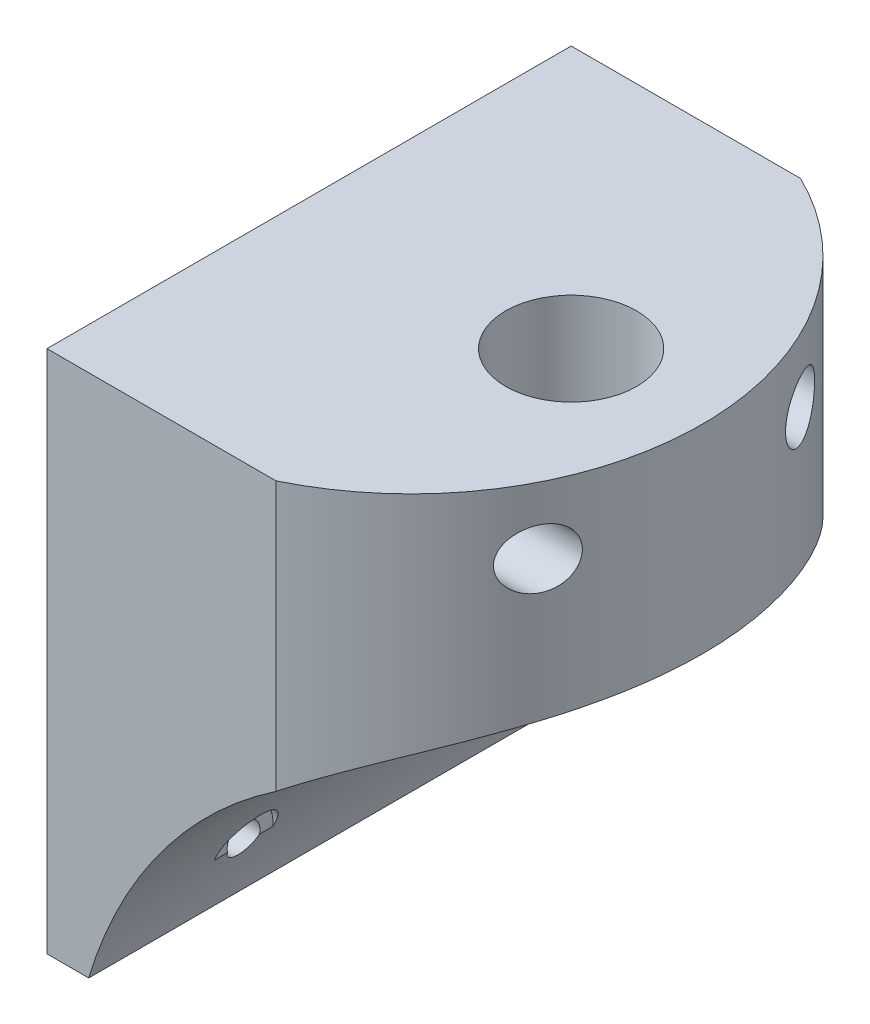
SolidWorks part; units mm, degrees
ref_plane "Front" through (0, 0, 0) normal (0, 0, 1) x (1, 0, 0)
ref_plane "Top" through (0, 0, 0) normal (0, 1, 0) x (1, 0, 0)
ref_plane "Right" through (0, 0, 0) normal (1, 0, 0) x (0, 0, -1)
sketch "Sketch1" plane through (0, 0, 0) normal (1, 0, 0) x (0, 0, -1)
  line L1 (-40, 40) -> (40, 40) construction
  line L2 (-40, 40) -> (-40, -40) construction
  line L3 (-40, -40) -> (40, -40) construction
  line L4 (40, 40) -> (40, -40) construction
  line L5 (-40, 40) -> (40, -40) construction
  line L6 (-40, -40) -> (40, 40) construction
  point P0 (0, 0)
  dimension "D1" = 80
  dimension "D2" = 80
sketch "Sketch2" plane through (0, 0, 0) normal (0, 1, 0) x (1, 0, 0)
  line L0 (0, 40) -> (0, -40)
  line L1 (0, -40) -> (0, 40) construction
  line L3 (0, 0) -> (40, 0) construction
  line L4 (0, 40) -> (35, 40)
  line L5 (0, 40) -> (0, -40)
  line L6 (0, -40) -> (34.9392, -40)
  circle A0 centre (40, 0) radius 10
  arc A1 (35, 40) -> (34.9392, -40) centre (15.5237, 0.0148) cw
  point P6 (60, -0.019)
  dimension "D2" = 20
  dimension "D1" = 40
  dimension "D3" = 80
  dimension "D4" = 60
extrude "Boss-Extrude1" add sketch "Sketch2" along normal mid plane 80
sketch "Sketch3" plane through (0, 0, 0) normal (0, 0, 1) x (1, 0, 0)
  line L0 (60, -40) -> (60, 40) construction
  line L1 (0, -40) -> (34.9392, -40) construction
  line L2 (60, 9.6308) -> (60, -40)
  line L3 (60, -40) -> (6.3708, -40)
  arc A0 (60, 9.6308) -> (6.3708, -40) centre (75.0602, -60.433) ccw
extrude "Cut-Extrude1" cut sketch "Sketch3" against normal mid plane 80
sketch "Sketch4" plane through (0, 0, 0) normal (1, 0, 0) x (0, 0, -1)
  line L1 (0, 40) -> (0, -40) construction
  line L2 (-40, 40) -> (40, 40) construction
  line L3 (-40, -40) -> (40, -40) construction
  line L4 (40, 0) -> (-40, 0) construction
  line L5 (40, 40) -> (40, -40) construction
  line L6 (-40, 40) -> (-40, -40) construction
  circle A0 centre (-20, 29.8466) radius 2.5
  circle A1 centre (20, 29.8466) radius 2.5
  circle A2 centre (20, -29.8466) radius 2.5
  circle A3 centre (-20, -29.8466) radius 2.5
  dimension "D1" = 20
extrude "Cut-Extrude2" cut sketch "Sketch4" along normal blind 80
ref_plane "Plane1" through (10, 0, 0) normal (1, 0, 0) x (0, 0, -1)
sketch "Sketch5" plane through (10, 0, 0) normal (1, 0, 0) x (0, 0, -1)
  line L0 (0, 40) -> (0, 0) construction
  line L1 (-40, 40) -> (40, 40) construction
  line L2 (0, 0) -> (-40, 0) construction
  line L3 (-40, 40) -> (-40, -40) construction
  circle A1 centre (20, 29.8466) radius 4.5
  circle A2 centre (-20, 29.8466) radius 4.5
  circle A3 centre (-20, 29.8466) radius 4.5
  circle A4 centre (20, -29.8466) radius 4.5
  circle A5 centre (-20, -29.8466) radius 4.5
  dimension "D1" = 2
extrude "Cut-Extrude3" cut sketch "Sketch5" along normal blind 80
